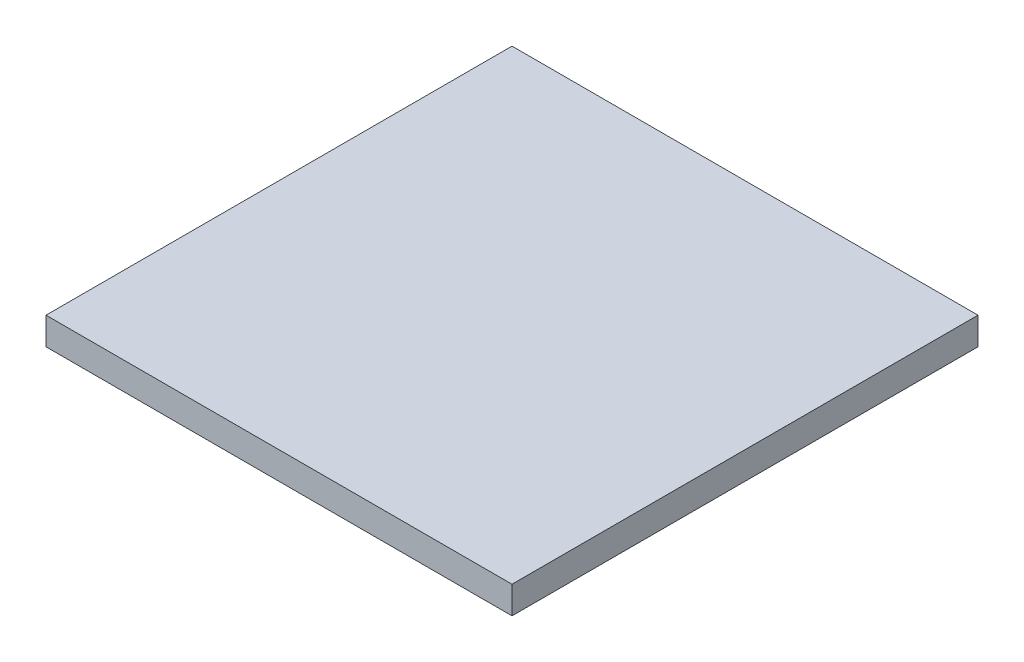
SolidWorks part; units mm, degrees
ref_plane "Front Plane" through (0, 0, 0) normal (0, 0, 1) x (1, 0, 0)
ref_plane "Top Plane" through (0, 0, 0) normal (0, 1, 0) x (1, 0, 0)
ref_plane "Right Plane" through (0, 0, 0) normal (1, 0, 0) x (0, 0, -1)
sketch "Sketch1" plane through (0, 0, 0) normal (0, 1, 0) x (1, 0, 0)
  line L1 (-50.1335, 31.4301) -> (17.8665, 31.4301)
  line L2 (-50.1335, 31.4301) -> (-50.1335, -36.5699)
  line L3 (-50.1335, -36.5699) -> (17.8665, -36.5699)
  line L4 (17.8665, 31.4301) -> (17.8665, -36.5699)
  dimension "Side 3" = 68
  dimension "Side 4" = 68
extrude "Boss-Extrude1" add sketch "Sketch1" along normal blind 4
